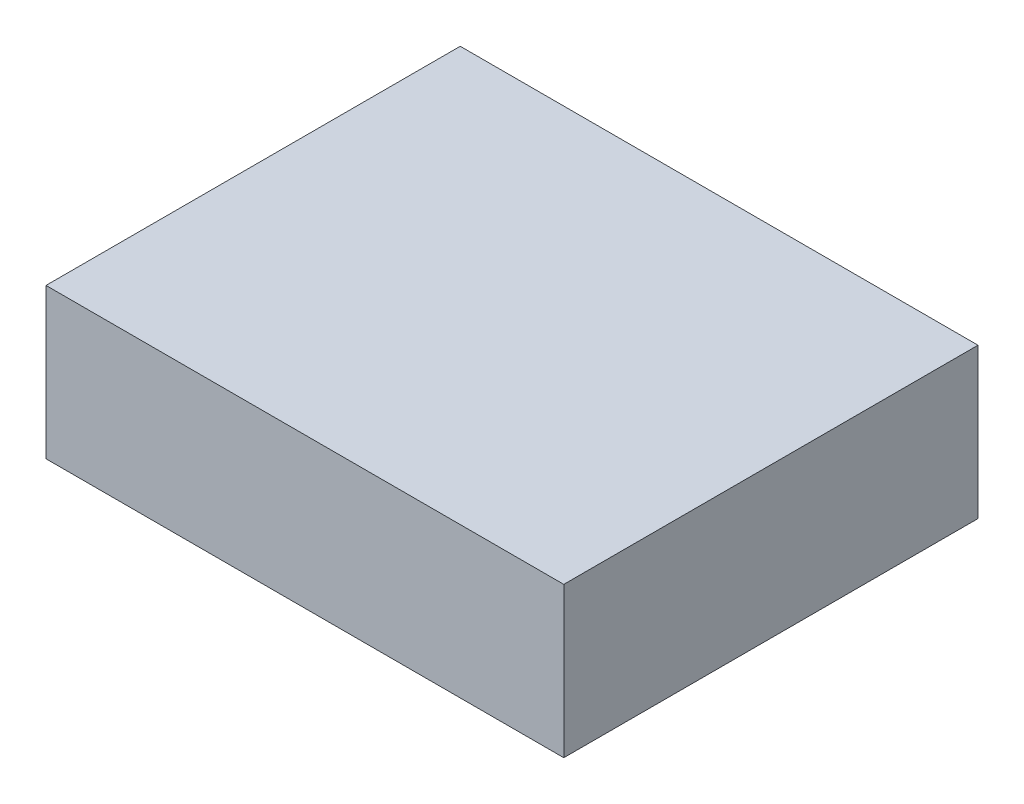
SolidWorks part; units mm, degrees
ref_plane "Front Plane" through (0, 0, 0) normal (0, 0, 1) x (1, 0, 0)
ref_plane "Top Plane" through (0, 0, 0) normal (0, 1, 0) x (1, 0, 0)
ref_plane "Right Plane" through (0, 0, 0) normal (1, 0, 0) x (0, 0, -1)
sketch "Sketch1" plane through (0, 0, 0) normal (0, 1, 0) x (1, 0, 0)
  line L1 (-50, 40) -> (50, 40)
  line L2 (-50, 40) -> (-50, -40)
  line L3 (-50, -40) -> (50, -40)
  line L4 (50, 40) -> (50, -40)
  line L5 (-50, 40) -> (50, -40) construction
  line L6 (-50, -40) -> (50, 40) construction
  point P0 (0, 0)
  dimension "D1" = 100
  dimension "D2" = 80
extrude "Boss-Extrude1" add sketch "Sketch1" along normal blind 29
